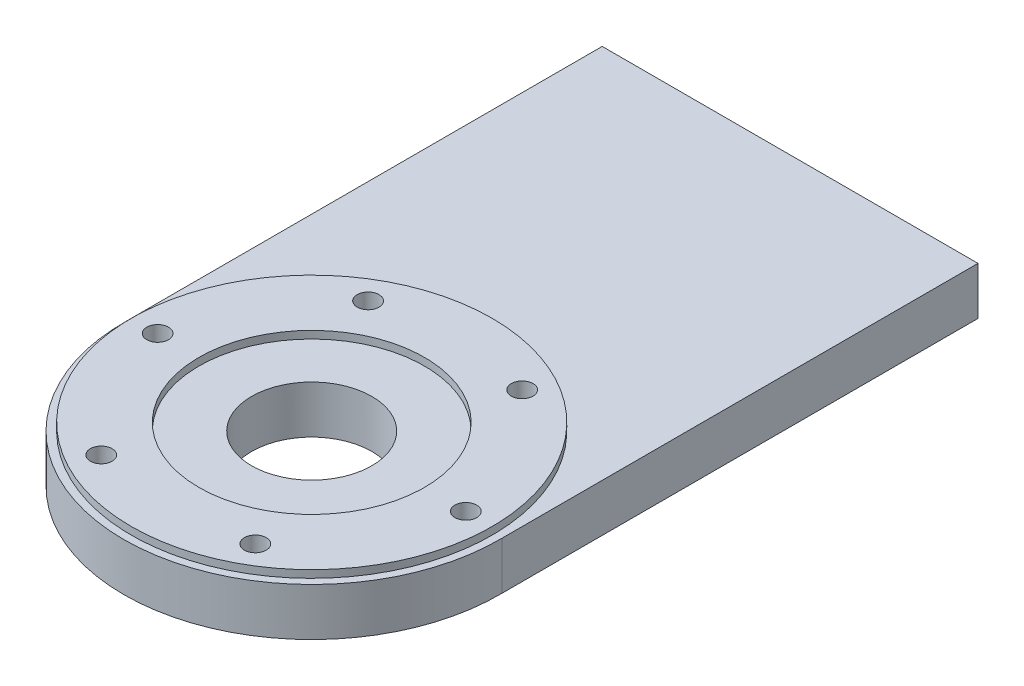
SolidWorks part; units mm, degrees
material "Aleación 6061"
ref_plane "Alzado" through (0, 0, 0) normal (0, 0, 1) x (1, 0, 0)
ref_plane "Planta" through (0, 0, 0) normal (0, 1, 0) x (1, 0, 0)
ref_plane "Vista lateral" through (0, 0, 0) normal (1, 0, 0) x (0, 0, -1)
sketch "Sk_Pared" plane through (0, 0, 0) normal (0, 1, 0) x (1, 0, 0)
  line L1 (-25, -489.65) -> (25, -489.65)
  line L2 (-25, -489.65) -> (-25, -426.35)
  line L3 (-25, -426.35) -> (25, -426.35)
  line L4 (25, -489.65) -> (25, -426.35)
  line L5 (-25, -489.65) -> (25, -426.35) construction
  line L6 (-25, -426.35) -> (25, -489.65) construction
  point P0 (0, -458)
  dimension "D1" = 50
  dimension "D2" = 63.3
  dimension "D3" = 458
extrude "Pared" add sketch "Sk_Pared" along normal blind 6.35 from offset 27.85
sketch "Sk_Cabeza" plane through (0, 0, 0) normal (0, 1, 0) x (1, 0, 0)
  circle A0 centre (0, -490) radius 25
  dimension "D1" = 50
  dimension "D2" = 490
extrude "Cabeza" add sketch "Sk_Cabeza" along normal blind 6.35 from offset 27.85
sketch "Sk_Asiento_1mm" plane through (0, 0, 0) normal (0, 1, 0) x (1, 0, 0)
  circle A0 centre (0, -490) radius 24
  circle A1 centre (0, -490) radius 15
  dimension "D1" = 48
  dimension "D3" = 30
  dimension "D2" = 490
  dimension "D4" = 490
extrude "Asiento_1mm" add sketch "Sk_Asiento_1mm" along normal blind 1 from offset 21.5
sketch "Sk_Paso_central" plane through (0, 0, 0) normal (0, 1, 0) x (1, 0, 0)
  circle A0 centre (0, -490) radius 8
  dimension "D1" = 16
  dimension "D2" = 490
extrude "Paso_central" cut sketch "Sk_Paso_central" along normal blind 7.35 from offset 27.85
sketch "Sk_Pasantes_M2-5_estator_J5" plane through (0, 0, 0) normal (0, 1, 0) x (1, 0, 0)
  circle A0 centre (20.5, -490) radius 1.45
  circle A1 centre (10.25, -507.7535) radius 1.45
  circle A2 centre (-10.25, -507.7535) radius 1.45
  circle A3 centre (-20.5, -490) radius 1.45
  circle A4 centre (-10.25, -472.2465) radius 1.45
  circle A5 centre (10.25, -472.2465) radius 1.45
  dimension "D1" = 2.9
  dimension "D4" = 2.9
  dimension "D7" = 2.9
  dimension "D10" = 2.9
  dimension "D13" = 2.9
  dimension "D16" = 2.9
  dimension "D2" = 20.5
  dimension "D3" = 490
  dimension "D5" = 10.25
  dimension "D6" = 507.7535
  dimension "D8" = 10.25
  dimension "D9" = 507.7535
  dimension "D11" = 20.5
  dimension "D12" = 490
  dimension "D14" = 10.25
  dimension "D15" = 472.2465
  dimension "D17" = 10.25
  dimension "D18" = 472.2465
extrude "Pasantes_M2-5_estator_J5" cut sketch "Sk_Pasantes_M2-5_estator_J5" along normal blind 7.35 from offset 27.85
sketch "Sk_Cajas_M2-5_J5" plane through (0, 0, 0) normal (0, 1, 0) x (1, 0, 0)
  circle A0 centre (10.25, -507.7535) radius 2.75
  circle A1 centre (-10.25, -507.7535) radius 2.75
  circle A2 centre (-10.25, -472.2465) radius 2.75
  circle A3 centre (10.25, -472.2465) radius 2.75
  dimension "D1" = 5.5
  dimension "D4" = 5.5
  dimension "D7" = 5.5
  dimension "D10" = 5.5
  dimension "D2" = 10.25
  dimension "D3" = 507.7535
  dimension "D5" = 10.25
  dimension "D6" = 507.7535
  dimension "D8" = 10.25
  dimension "D9" = 472.2465
  dimension "D11" = 10.25
  dimension "D12" = 472.2465
extrude "Cajas_M2-5_J5" cut sketch "Sk_Cajas_M2-5_J5" along normal blind 2.5 from offset 27.85
sketch "Sk_Pasantes_M4_angulos" plane through (0, 0, 0) normal (0, 1, 0) x (1, 0, 0)
  circle A0 centre (-20, -437.11) radius 2.25
  circle A1 centre (20, -437.11) radius 2.25
  dimension "D1" = 4.5
  dimension "D4" = 4.5
  dimension "D2" = 20
  dimension "D3" = 437.11
  dimension "D5" = 20
  dimension "D6" = 437.11
sketch "Sk_Rosca_M3_desde_abajo" plane through (0, 0, 426.35) normal (0, 0, -1) x (-1, 0, 0)
  circle A0 centre (15, -24.675) radius 1.25
  circle A1 centre (-15, -24.675) radius 1.25
extrude "Rosca_M3_desde_abajo" cut sketch "Sk_Rosca_M3_desde_abajo" against normal blind 9
